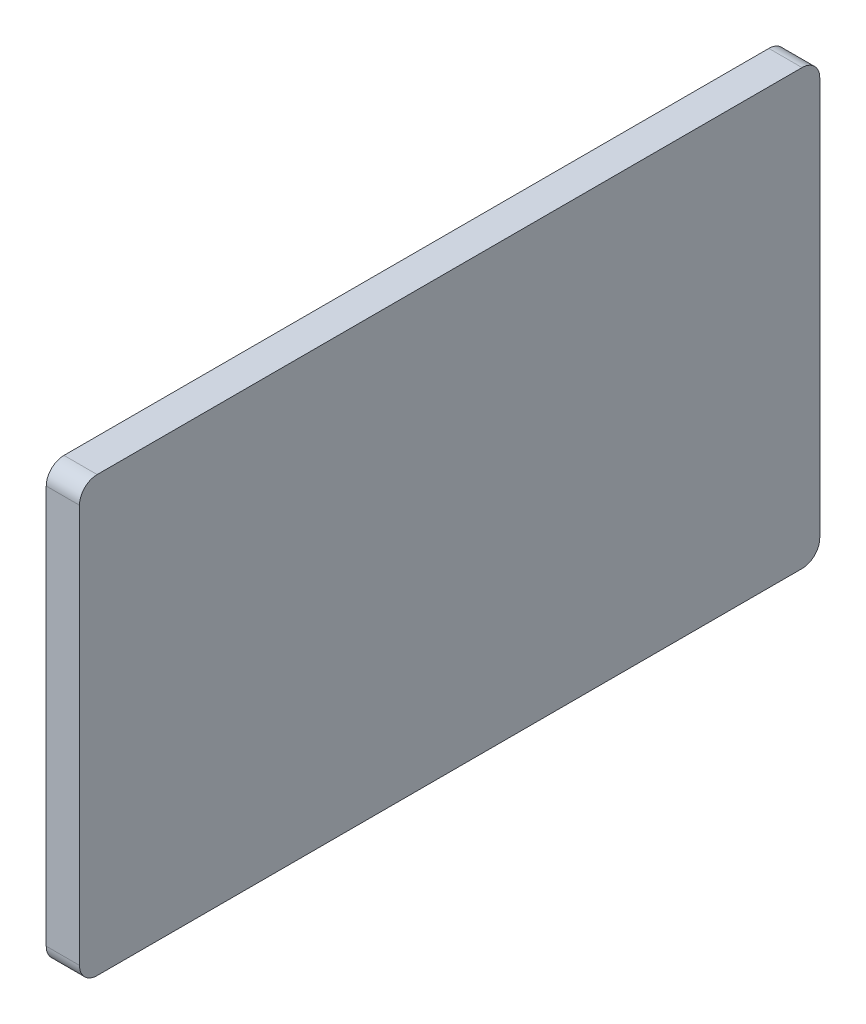
SolidWorks part; units mm, degrees
material "6061-T6 (SS)"
ref_plane "Front Plane" through (0, 0, 0) normal (0, 0, 1) x (1, 0, 0)
ref_plane "Top Plane" through (0, 0, 0) normal (0, 1, 0) x (1, 0, 0)
ref_plane "Right Plane" through (0, 0, 0) normal (1, 0, 0) x (0, 0, -1)
sketch "Sketch1" plane through (0, 0, 0) normal (1, 0, 0) x (0, 0, -1)
  line L1 (-106.172, -62.23) -> (106.172, -62.23)
  line L2 (-106.172, -62.23) -> (-106.172, 62.23)
  line L3 (-106.172, 62.23) -> (106.172, 62.23)
  line L4 (106.172, -62.23) -> (106.172, 62.23)
  line L5 (-106.172, -62.23) -> (106.172, 62.23) construction
  line L6 (-106.172, 62.23) -> (106.172, -62.23) construction
  point P0 (0, 0)
  dimension "D1" = 212.344
  dimension "D2" = 124.46
extrude "Boss-Extrude1" add sketch "Sketch1" along normal blind 9.525
fillet "Fillet1" radius 5.08 4 edges at (4.7625, -62.23, -106.172) (4.7625, -62.23, 106.172) (4.7625, 62.23, -106.172) (4.7625, 62.23, 106.172)
